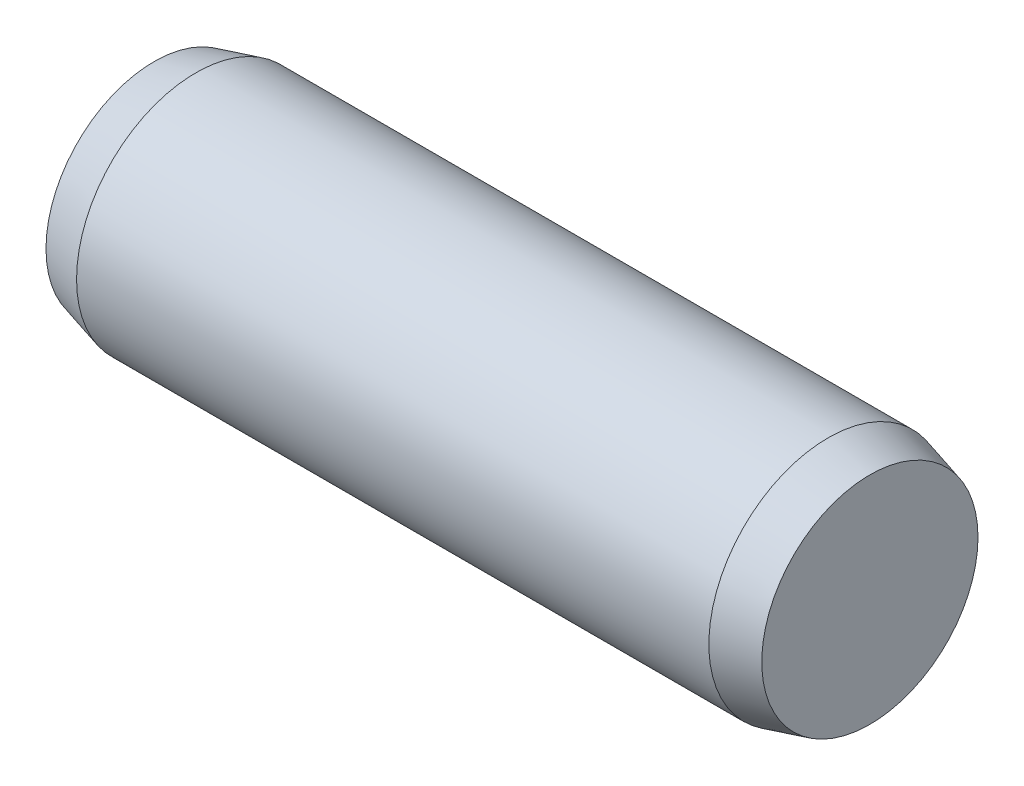
SolidWorks part; units mm, degrees
ref_plane "Front Plane" through (0, 0, 0) normal (0, 0, 1) x (1, 0, 0)
ref_plane "Top Plane" through (0, 0, 0) normal (0, 1, 0) x (1, 0, 0)
ref_plane "Right Plane" through (0, 0, 0) normal (1, 0, 0) x (0, 0, -1)
sketch "Sketch1" plane through (0, 0, 0) normal (0, 0, 1) x (1, 0, 0)
  line L0 (-2.65, 0) -> (2.65, 0) construction
  line L1 (2.65, 1) -> (2.65, -1) construction
  line L2 (-2.65, 1) -> (-2.65, -1) construction
  line L3 (3, 1) -> (3, -1) construction
  line L4 (-3, 1) -> (-3, -1) construction
  line L5 (-2.65, 0) -> (-3, 0) construction
  line L6 (2.65, 0) -> (3, 0) construction
  dimension "Dia" = 2
  dimension "C" = 0.35
  dimension "D1" = 0.35
  dimension "Length" = 6
sketch "Sketch2" plane through (0, 0, 0) normal (1, 0, 0) x (0, 0, -1)
  circle A0 centre (0, 0) radius 1
extrude "Extrude1" add sketch "Sketch2" against normal up to vertex (2.65 mm away) and the other way up to vertex (2.65 mm away) up to point (-2.65, 1, 0) other way up to point (2.65, 1, 0)
sketch "Sketch3" plane through (2.65, 0, 0) normal (1, 0, 0) x (0, 0, -1)
  circle A1 centre (0, 0) radius 1
  circle A2 centre (0, 0) radius 1
  dimension "D1" = 0
extrude "Extrude2" add sketch "Sketch3" along normal up to vertex (0.35 mm away) draft 15 up to point (3, 0, 0)
sketch "Sketch4" plane through (-2.65, 0, 0) normal (-1, 0, 0) x (0, 0, 1)
  circle A1 centre (0, 0) radius 1
  circle A2 centre (0, 0) radius 1
  dimension "D1" = 0
extrude "Extrude3" add sketch "Sketch4" along normal up to vertex (0.35 mm away) draft 15 up to point (-3, 0, 0)
equation "\"D1@Sketch1\" = \"C@Sketch1\""
